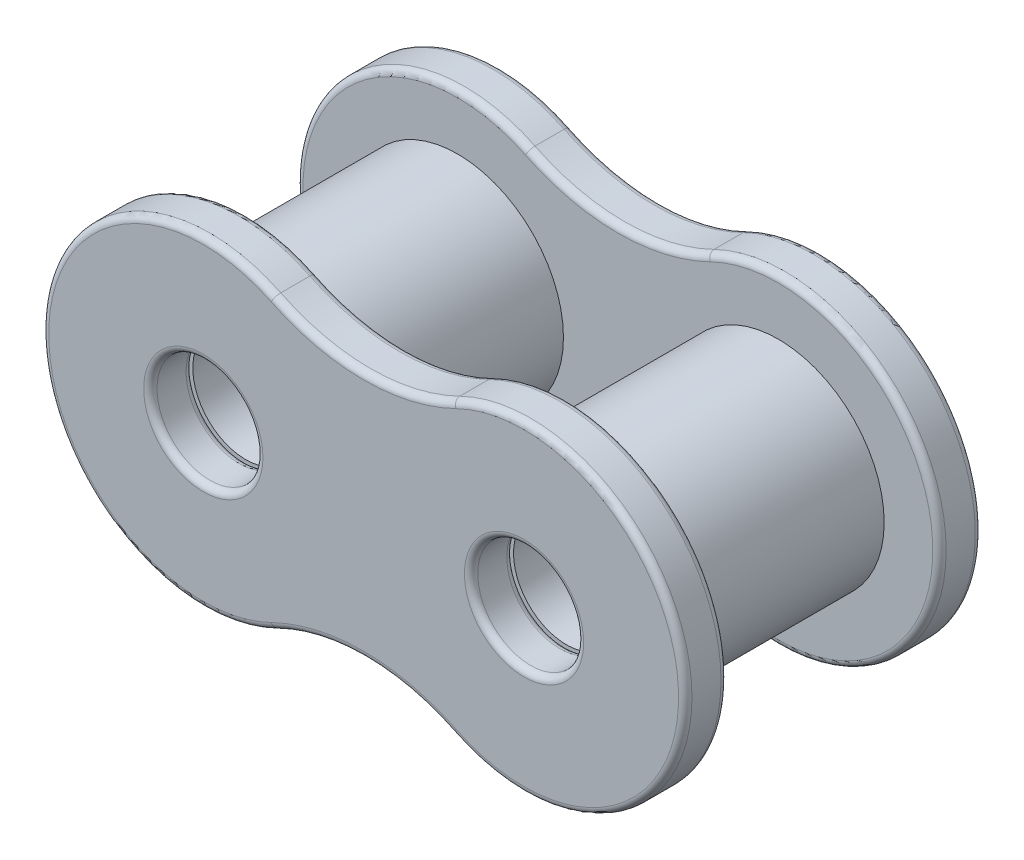
SolidWorks part; units mm, degrees
ref_plane "Plan de face" through (0, 0, 0) normal (0, 0, 1) x (1, 0, 0)
ref_plane "Plan de dessus" through (0, 0, 0) normal (0, 1, 0) x (1, 0, 0)
ref_plane "Plan de droite" through (0, 0, 0) normal (1, 0, 0) x (0, 0, -1)
sketch "Esquisse1" plane through (0, 0, 0) normal (0, 0, 1) x (1, 0, 0)
  line L3 (-4.0188, 0) -> (-6, 0) construction
  circle A0 centre (-6, 0) radius 1.9812
  arc A1 (-3.3489, 5.4187) -> (-3.3489, -5.4187) centre (-6, 0) ccw
  arc A2 (3.3489, 5.4187) -> (3.3489, -5.4187) centre (6, 0) cw
  circle A3 centre (6, 0) radius 1.9812
  arc A4 (-3.3489, 5.4187) -> (3.3489, 5.4187) centre (0, 12.2637) ccw
  arc A5 (-3.3489, -5.4187) -> (3.3489, -5.4187) centre (0, -12.2637) cw
  dimension "D1" = 3.9624
  dimension "D2" = 12.065
extrude "Boss.-Extru.1" add sketch "Esquisse1" along normal blind 1.5875
sketch "Esquisse2" plane through (0, 0, 0) normal (0, 0, 1) x (1, 0, 0)
  circle A0 centre (-6, 0) radius 1.9812 construction
  circle A1 centre (-6, 0) radius 1.9812
fillet "Congé1" radius 0.25 12 edges at (4.0188, 0, 0) (-4.0188, 0, 0) (-12.0325, 0, 0) (0, -4.6434, 0) (12.0325, 0, 0) (0, 4.6434, 0) (4.0188, 0, 1.5875) (12.0325, 0, 1.5875) (0, -4.6434, 1.5875) (-12.0325, 0, 1.5875) (0, 4.6434, 1.5875) (-4.0188, 0, 1.5875)
sketch "Esquisse3" plane through (0, 0, 1.5875) normal (0, 0, 1) x (1, 0, 0)
  circle A0 centre (-6, 0) radius 1.9812
  circle A1 centre (-6, 0) radius 3.9624
extrude "Boss.-Extru.2" add sketch "Esquisse3" along normal blind 7.9248
mirror "Symétrie1" about plane through (0, 0, 0) normal (1, 0, 0) of "Boss.-Extru.2"
ref_plane "Plan2" through (0, 0, 5.5499) normal (0, 0, 1) x (1, 0, 0)
mirror "Symétrie3" about plane through (0, 0, 5.5499) normal (0, 0, 1) of bodies 103
